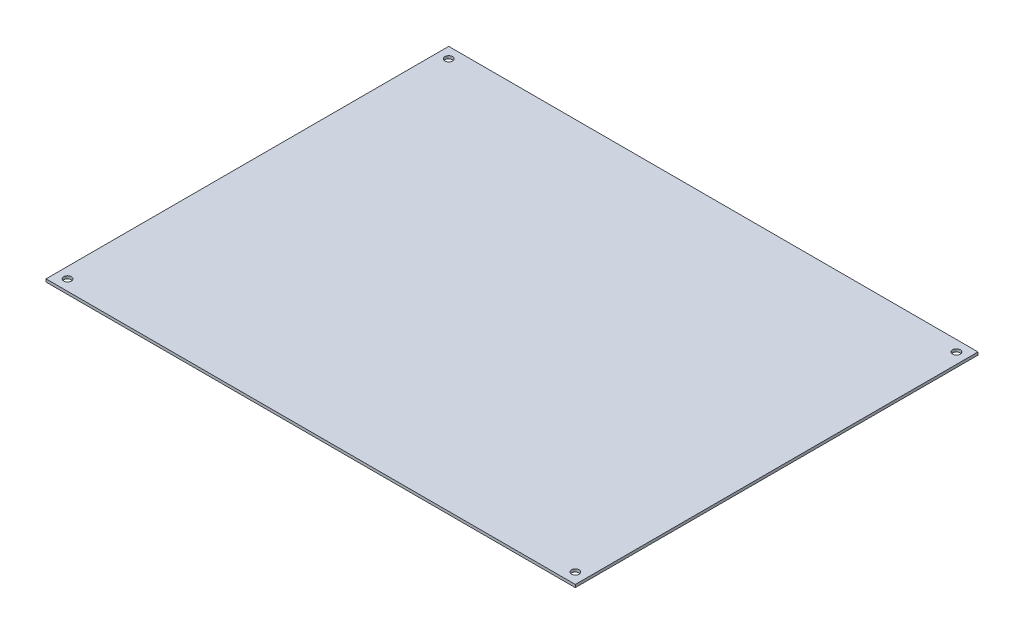
SolidWorks part; units mm, degrees
ref_plane "Front Plane" through (0, 0, 0) normal (0, 0, 1) x (1, 0, 0)
ref_plane "Top Plane" through (0, 0, 0) normal (0, 1, 0) x (1, 0, 0)
ref_plane "Right Plane" through (0, 0, 0) normal (1, 0, 0) x (0, 0, -1)
sketch "Sketch4" plane through (0, 0, 0) normal (0, 1, 0) x (1, 0, 0)
  line L1 (-190.25, 144.75) -> (190.25, 144.75)
  line L2 (-190.25, 144.75) -> (-190.25, -144.75)
  line L3 (-190.25, -144.75) -> (190.25, -144.75)
  line L4 (190.25, 144.75) -> (190.25, -144.75)
extrude "Boss-Extrude1" add sketch "Sketch4" along normal blind 2
sketch "Sketch5" plane through (0, 2, 0) normal (0, 1, 0) x (1, 0, 0)
  circle A0 centre (182.5, 137) radius 2.75
extrude "Cut-Extrude1" cut sketch "Sketch5" against normal through all
mirror "Mirror1" about plane through (0, 0, 0) normal (1, 0, 0) of "Cut-Extrude1"
mirror "Mirror2" about plane through (0, 0, 0) normal (0, 0, 1) of "Mirror1", "Cut-Extrude1"
